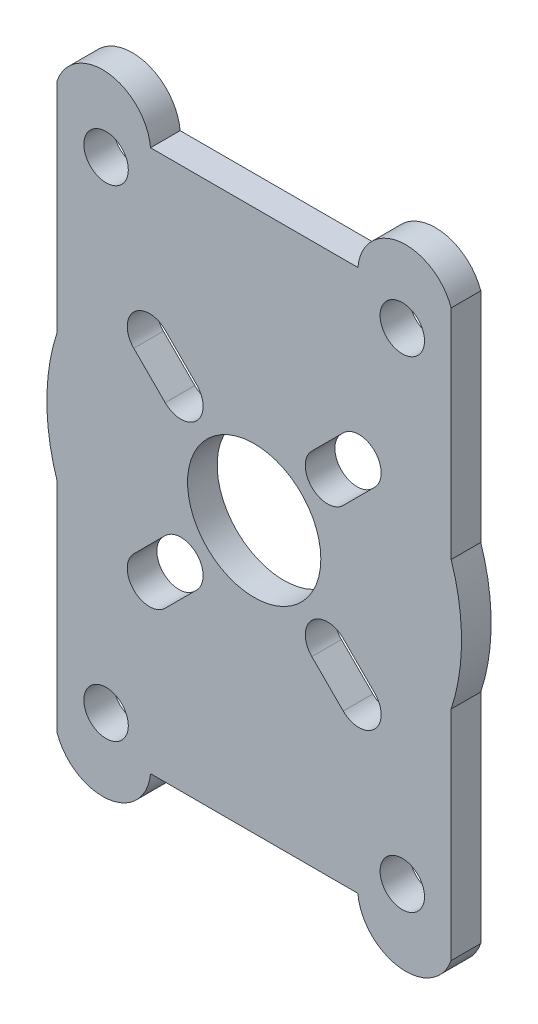
SolidWorks part; units mm, degrees
ref_plane "Front Plane" through (0, 0, 0) normal (0, 0, 1) x (1, 0, 0)
ref_plane "Top Plane" through (0, 0, 0) normal (0, 1, 0) x (1, 0, 0)
ref_plane "Right Plane" through (0, 0, 0) normal (1, 0, 0) x (0, 0, -1)
sketch "Sketch1" plane through (0, 0, 0) normal (0, 0, 1) x (1, 0, 0)
  line L0 (-13.3, 4.3715) -> (-13.3, 18.3)
  line L1 (-7, -18.3) -> (7, -18.3)
  line L2 (-13.3, -18.3) -> (-13.3, -4.3715)
  line L3 (-7, 18.3) -> (7, 18.3)
  line L4 (13.3, -18.3) -> (13.3, -4.3715)
  line L5 (-13.3, -18.3) -> (13.3, 18.3) construction
  line L6 (-13.3, 18.3) -> (13.3, -18.3) construction
  line L7 (13.3, 4.3715) -> (13.3, 18.3)
  line L8 (-13.3, 18.3) -> (-13.3, 19.0841)
  line L9 (0, 0) -> (7.8247, 0) construction
  line L10 (0, 0) -> (0, -6.4089) construction
  line L11 (13.3, 18.3) -> (13.3, 19.0841)
  line L12 (13.3, -18.3) -> (13.3, -19.0841)
  line L13 (-13.3, -18.3) -> (-13.3, -19.0841)
  arc A0 (-13.3, 4.3715) -> (-13.3, -4.3715) centre (0, 0) ccw
  arc A1 (13.3, -4.3715) -> (13.3, 4.3715) centre (0, 0) ccw
  arc A3 (-7, 18.3) -> (-13.3, 19.0841) centre (-10.2361, 18) ccw
  arc A4 (7, 18.3) -> (13.3, 19.0841) centre (10.2361, 18) cw
  arc A5 (7, -18.3) -> (13.3, -19.0841) centre (10.2361, -18) ccw
  arc A6 (-7, -18.3) -> (-13.3, -19.0841) centre (-10.2361, -18) cw
  point P0 (0, 0)
  point P14 (-10.2361, 21.25)
  point P15 (-7, 18.3)
  dimension "D3" = 28
  dimension "D1" = 26.6
  dimension "D2" = 36.6
  dimension "D5" = 21.25
  dimension "D6" = 7
extrude "Boss-Extrude1" add sketch "Sketch1" along normal blind 2
sketch "Sketch2" plane through (0, 0, 2) normal (0, 0, 1) x (1, 0, 0)
  line L0 (0, 0) -> (8.0773, 0) construction
  line L1 (0, 0) -> (0, 10.1803) construction
  line L2 (-8.5, 16.25) -> (8.5, 16.25) construction
  line L3 (-10, -14.75) -> (-10, 14.75) construction
  line L4 (4.9497, 4.9497) -> (7.0711, 7.0711) construction
  line L5 (3.8891, 6.0104) -> (6.0104, 8.1317)
  line L6 (6.0104, 3.8891) -> (8.1317, 6.0104)
  line L7 (4.9497, 4.9497) -> (0, 0) construction
  line L8 (4.9497, -4.9497) -> (7.0711, -7.0711) construction
  line L9 (6.0104, -3.8891) -> (8.1317, -6.0104)
  line L10 (3.8891, -6.0104) -> (6.0104, -8.1317)
  line L11 (-4.9497, -4.9497) -> (-7.0711, -7.0711) construction
  line L12 (-3.8891, -6.0104) -> (-6.0104, -8.1317)
  line L13 (-6.0104, -3.8891) -> (-8.1317, -6.0104)
  line L14 (-4.9497, 4.9497) -> (-7.0711, 7.0711) construction
  line L15 (-6.0104, 3.8891) -> (-8.1317, 6.0104)
  line L16 (-3.8891, 6.0104) -> (-6.0104, 8.1317)
  circle A0 centre (0, 0) radius 4.5
  circle A1 centre (-10, 16.25) radius 1.5
  circle A2 centre (10, 16.25) radius 1.5
  circle A3 centre (-10, -16.25) radius 1.5
  circle A4 centre (10, -16.25) radius 1.5
  arc A5 (3.8891, 6.0104) -> (6.0104, 3.8891) centre (4.9497, 4.9497) ccw
  arc A6 (8.1317, 6.0104) -> (6.0104, 8.1317) centre (7.0711, 7.0711) ccw
  arc A7 (6.0104, -3.8891) -> (3.8891, -6.0104) centre (4.9497, -4.9497) ccw
  arc A8 (6.0104, -8.1317) -> (8.1317, -6.0104) centre (7.0711, -7.0711) ccw
  arc A9 (-3.8891, -6.0104) -> (-6.0104, -3.8891) centre (-4.9497, -4.9497) ccw
  arc A10 (-8.1317, -6.0104) -> (-6.0104, -8.1317) centre (-7.0711, -7.0711) ccw
  arc A11 (-6.0104, 3.8891) -> (-3.8891, 6.0104) centre (-4.9497, 4.9497) ccw
  arc A12 (-6.0104, 8.1317) -> (-8.1317, 6.0104) centre (-7.0711, 7.0711) ccw
  point P18 (0, 16.25)
  point P19 (-10, 0)
  point P21 (6.0104, 6.0104)
  point P26 (3.8891, 3.8891)
  point P33 (6.0104, -6.0104)
  point P40 (-6.0104, -6.0104)
  point P47 (-6.0104, 6.0104)
  point P52 (0, 0)
  dimension "D1" = 9
  dimension "D2" = 3
  dimension "D5" = 1.5
  dimension "D3" = 17
  dimension "D4" = 29.5
  dimension "D6" = 45
  dimension "D7" = 5.5
  dimension "D8" = 3
  dimension "D9" = 4
extrude "Cut-Extrude1" cut sketch "Sketch2" against normal blind 2
